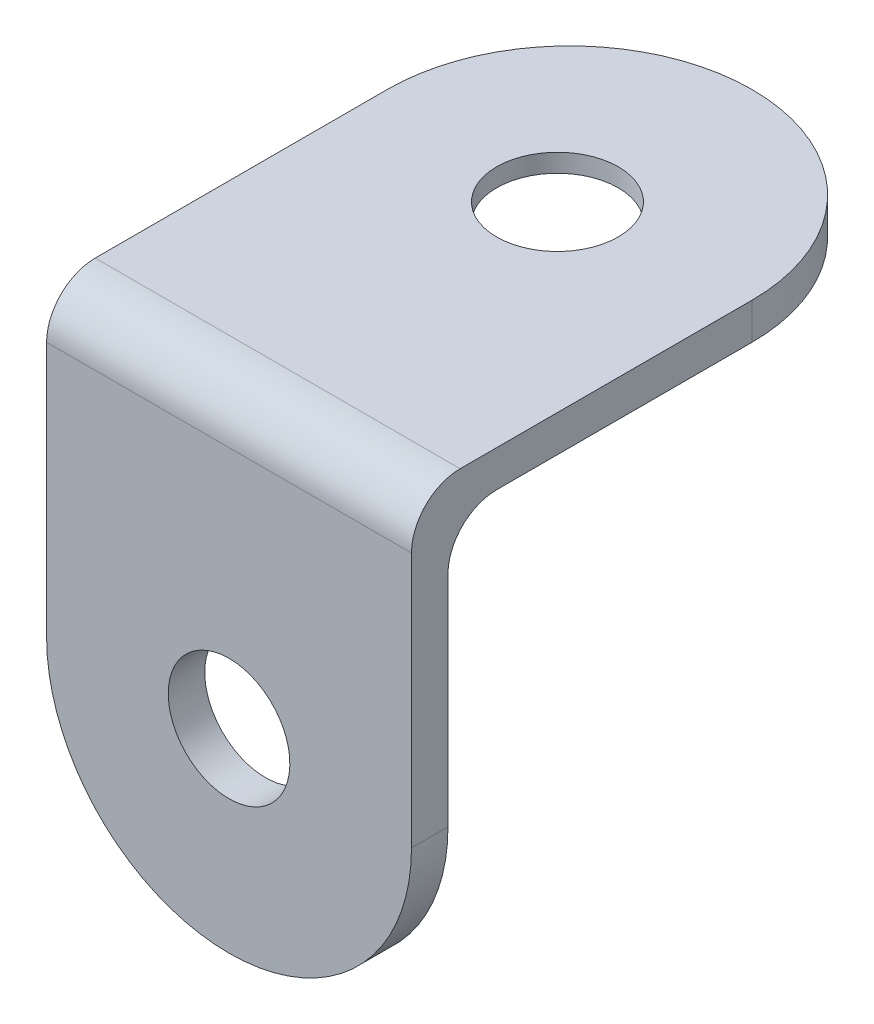
SolidWorks part; units mm, degrees
material "Alloy Steel"
ref_plane "Front Plane" through (0, 0, 0) normal (0, 0, 1) x (1, 0, 0)
ref_plane "Top Plane" through (0, 0, 0) normal (0, 1, 0) x (1, 0, 0)
ref_plane "Right Plane" through (0, 0, 0) normal (1, 0, 0) x (0, 0, -1)
sketch "Sketch1" plane through (0, 0, 0) normal (0, 1, 0) x (1, 0, 0)
  line L0 (-7.5, 0) -> (7.5, 0)
  line L1 (0, 0) -> (0, 20) construction
  line L2 (-7.5, 0) -> (-7.5, 12.5)
  line L3 (7.5, 0) -> (7.5, 12.5)
  arc A0 (7.5, 12.5) -> (-7.5, 12.5) centre (0, 12.5) ccw
  circle A2 centre (0, 12) radius 2.5
  point P4 (0, 0)
  dimension "D4" = 8
  dimension "D1" = 15
  dimension "D2" = 20
  dimension "D3" = 12.5
extrude "Boss-Extrude1" add sketch "Sketch1" along normal blind 1.5
ref_plane "Plane1" through (0, 0, 0) normal (0, 0, 1) x (1, 0, 0)
pattern_circular "CirPattern1" count 2 every 90 about axis through (-7.5, 1.5, 0) along (1, 0, 0) of "Boss-Extrude1"
fillet "Fillet1" radius 2 2 edges at (0, 0, 0) (0, 1.5, 1.5)
ref_plane "Plane2" through (0, 0.75, 0) normal (0, -1, 0) x (-1, 0, 0)
sketch "Sketch3" plane through (0, 0.75, 0) normal (0, -1, 0) x (-1, 0, 0)
  circle A0 centre (0, 12) radius 2.5
extrude "Cut-Extrude2" cut sketch "Sketch3" along normal up to surface (0.75 mm away) draft 60 contours A0
